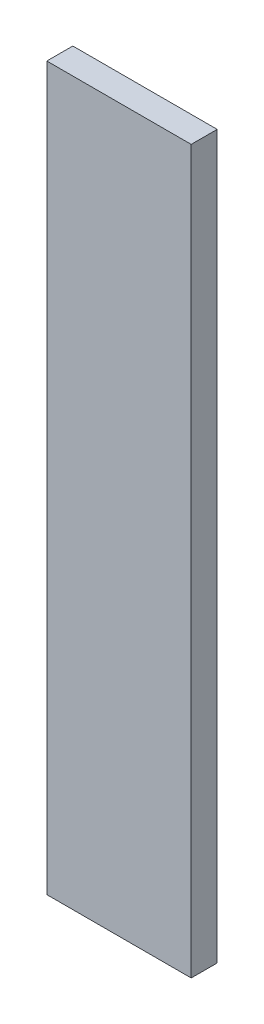
SolidWorks part; units mm, degrees
ref_plane "Front Plane" through (0, 0, 0) normal (0, 0, 1) x (1, 0, 0)
ref_plane "Top Plane" through (0, 0, 0) normal (0, 1, 0) x (1, 0, 0)
ref_plane "Right Plane" through (0, 0, 0) normal (1, 0, 0) x (0, 0, -1)
sketch "Sketch1" plane through (0, 0, 0) normal (0, 1, 0) x (1, 0, 0)
  line L1 (0, 0) -> (100, 0)
  line L2 (0, 0) -> (0, 18)
  line L3 (0, 18) -> (100, 18)
  line L4 (100, 0) -> (100, 18)
  dimension "D1" = 18
  dimension "D2" = 100
extrude "Boss-Extrude1" add sketch "Sketch1" along normal blind 500
